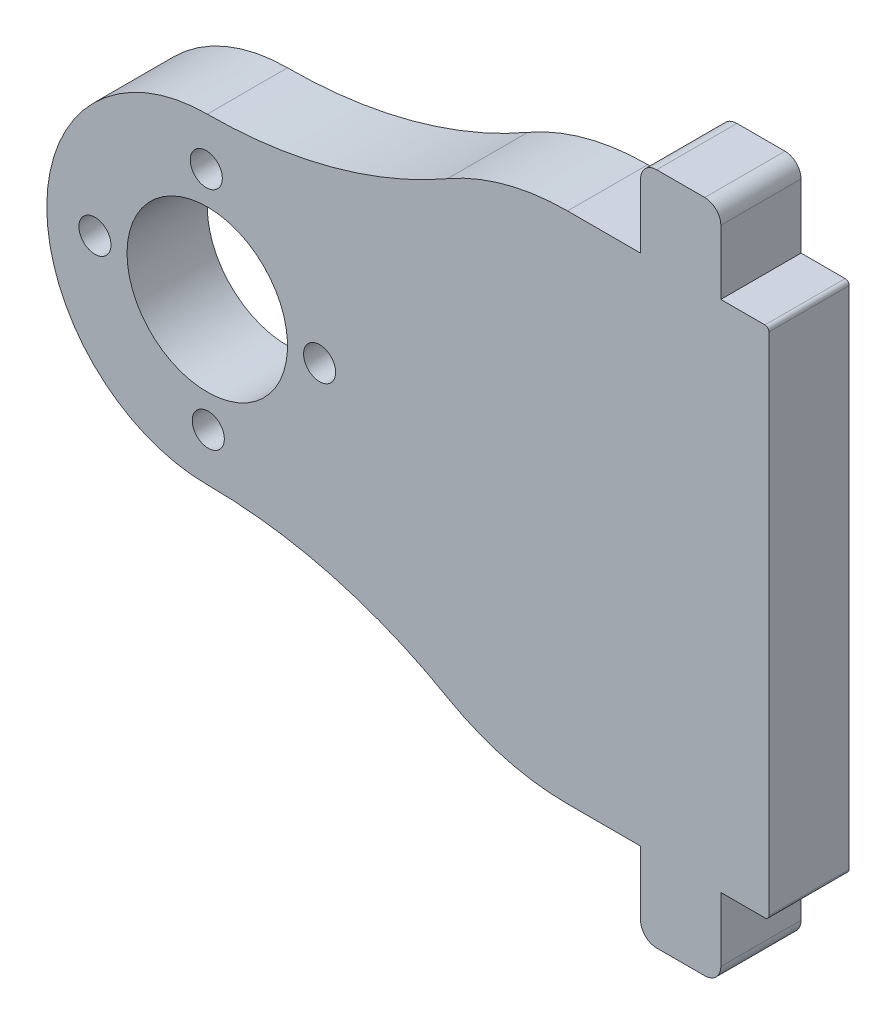
SolidWorks part; units mm, degrees
ref_plane "Front Plane" through (0, 0, 0) normal (0, 0, 1) x (1, 0, 0)
ref_plane "Top Plane" through (0, 0, 0) normal (0, 1, 0) x (1, 0, 0)
ref_plane "Right Plane" through (0, 0, 0) normal (1, 0, 0) x (0, 0, -1)
sketch "Sketch1" plane through (0, 0, 0) normal (0, 0, 1) x (1, 0, 0)
  line L0 (19.25, -21) -> (14.5, -21)
  line L1 (14.5, -21) -> (14.5, -16)
  line L2 (14.5, -16) -> (13.4072, -16)
  line L3 (13.4072, -16) -> (9.9499, -16)
  line L4 (22.25, -16) -> (19.75, -16)
  line L5 (19.5, -16.25) -> (19.5, -20.75)
  line L6 (9.9499, 16) -> (13.4072, 16)
  line L7 (13.4072, 16) -> (14.5, 16)
  line L8 (14.5, 16) -> (14.5, 21)
  line L9 (14.5, 21) -> (19.25, 21)
  line L10 (19.5, 20.75) -> (19.5, 16.25)
  line L11 (19.75, 16) -> (22.25, 16)
  line L12 (22.5, 15.75) -> (22.5, -15.75)
  arc A0 (-12.5, 10) -> (-12.5, -10) centre (-12.5, 0) ccw
  arc A1 (2.4666, -14) -> (-12.5, -10) centre (-12.5, -40) ccw
  arc A2 (2.4666, -14) -> (9.9499, -16) centre (9.9499, -1) ccw
  arc A3 (19.75, -16) -> (19.5, -16.25) centre (19.75, -16.25) ccw
  arc A4 (19.25, -21) -> (19.5, -20.75) centre (19.25, -20.75) ccw
  arc A5 (-12.5, 10) -> (2.4666, 14) centre (-12.5, 40) ccw
  arc A6 (9.9499, 16) -> (2.4666, 14) centre (9.9499, 1) ccw
  arc A7 (19.5, 20.75) -> (19.25, 21) centre (19.25, 20.75) ccw
  arc A8 (19.5, 16.25) -> (19.75, 16) centre (19.75, 16.25) ccw
  arc A9 (22.5, 15.75) -> (22.25, 16) centre (22.25, 15.75) ccw
  arc A10 (22.25, -16) -> (22.5, -15.75) centre (22.25, -15.75) ccw
  circle A12 centre (-19.5, -0.0625) radius 1
  circle A14 centre (-12.5625, 7) radius 1
  circle A16 centre (-5.5, 0.0625) radius 1
  circle A18 centre (-12.5, 0) radius 1.5
  circle A19 centre (-12.4375, -7) radius 1
extrude "Boss-Extrude1" add sketch "Sketch1" along normal blind 5
sketch "Sketch2" plane through (0, 0, 0) normal (0, 0, -1) x (-1, 0, 0)
  circle A0 centre (12.5, 0) radius 5
  circle A1 centre (12.5, 0) radius 1.5 construction
  dimension "D1" = 10
extrude "Cut-Extrude1" cut sketch "Sketch2" against normal blind 5
sketch "Sketch3" plane through (0, 0, 0) normal (0, 0, -1) x (-1, 0, 0)
  line L0 (-19.5, 16.25) -> (-19.5, 20.75) construction
  line L1 (-19.5, 22.5453) -> (-20.9356, 22.5453)
  line L2 (-19.5, 22.5453) -> (-19.5, 16)
  line L3 (-19.5, 16) -> (-20.9356, 16)
  line L4 (-20.9356, 22.5453) -> (-20.9356, 16)
  line L5 (-19.5, -16) -> (-22.7695, -16)
  line L6 (-19.5, -16) -> (-19.5, -22.0303)
  line L7 (-19.5, -22.0303) -> (-22.7695, -22.0303)
  line L8 (-22.7695, -16) -> (-22.7695, -22.0303)
  line L9 (-22.25, 16) -> (-19.75, 16) construction
  line L10 (-19.5, -20.75) -> (-19.5, -16.25) construction
  line L11 (-19.75, -16) -> (-22.25, -16) construction
extrude "Cut-Extrude2" cut sketch "Sketch3" against normal blind 5
sketch "Sketch4" plane through (0, 0, 0) normal (0, 0, -1) x (-1, 0, 0)
  line L0 (-19.5, -20.75) -> (-19.5, -16) construction
  line L1 (-15.7501, 21) -> (-19.5, 21)
  line L2 (-15.7501, 21) -> (-15.7501, -21)
  line L3 (-15.7501, -21) -> (-19.5, -21)
  line L4 (-19.5, 21) -> (-19.5, -21)
  line L5 (-19.25, 21) -> (-14.5, 21) construction
  line L6 (-14.5, -21) -> (-19.25, -21) construction
extrude "Boss-Extrude2" add sketch "Sketch4" against normal blind 5
fillet "Fillet1" radius 1 4 edges at (19.5, -21, 2.5) (14.5, -21, 2.5) (19.5, 21, 2.5) (14.5, 21, 2.5)
